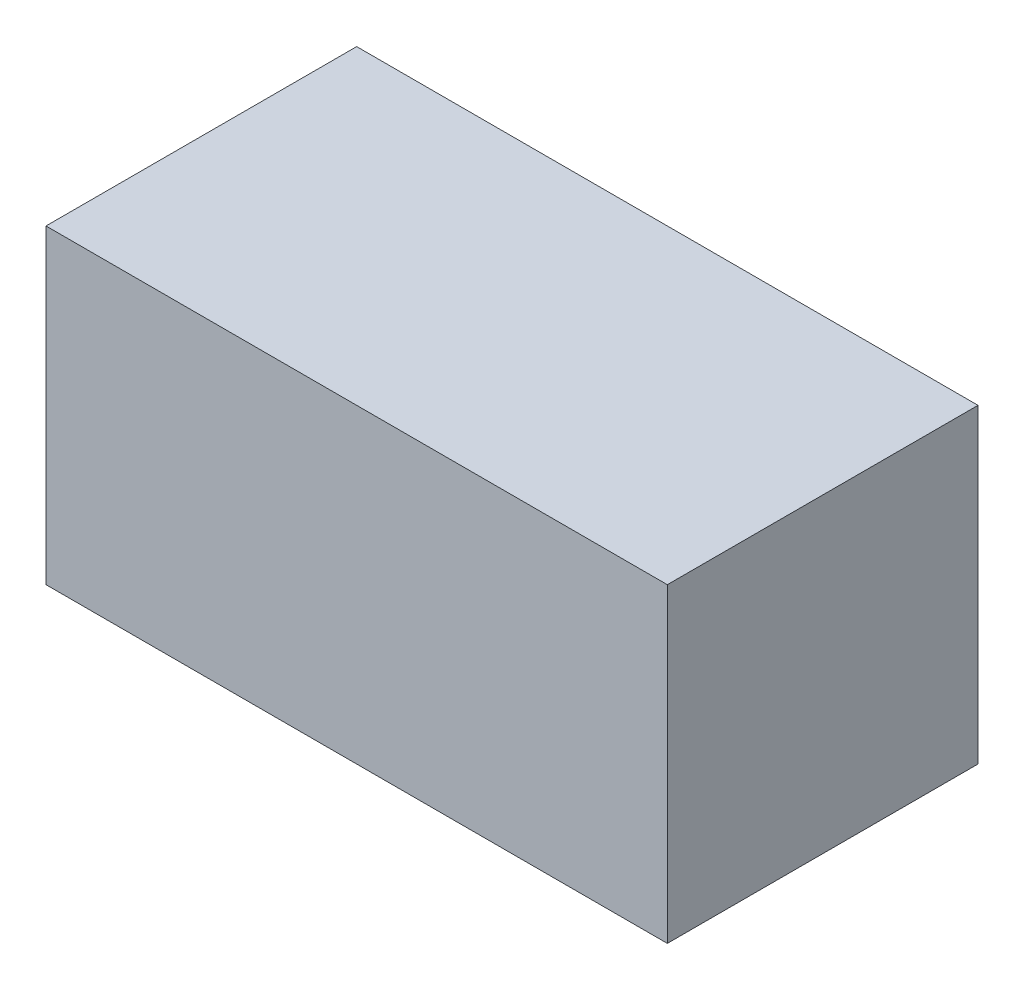
SolidWorks part; units mm, degrees
material "1.0037 (S235JR)"
ref_plane "Plan de face" through (0, 0, 0) normal (0, 0, 1) x (1, 0, 0)
ref_plane "Plan de dessus" through (0, 0, 0) normal (0, 1, 0) x (1, 0, 0)
ref_plane "Plan de droite" through (0, 0, 0) normal (1, 0, 0) x (0, 0, -1)
sketch "Esquisse1" plane through (0, 0, 0) normal (0, 0, 1) x (1, 0, 0)
  line L1 (-10, -5) -> (10, -5)
  line L2 (-10, -5) -> (-10, 5)
  line L3 (-10, 5) -> (10, 5)
  line L4 (10, -5) -> (10, 5)
  line L5 (-10, -5) -> (10, 5) construction
  line L6 (-10, 5) -> (10, -5) construction
  point P0 (0, 0)
  dimension "D1" = 20
  dimension "D2" = 10
extrude "Boss.-Extru.1" add sketch "Esquisse1" along normal blind 10
